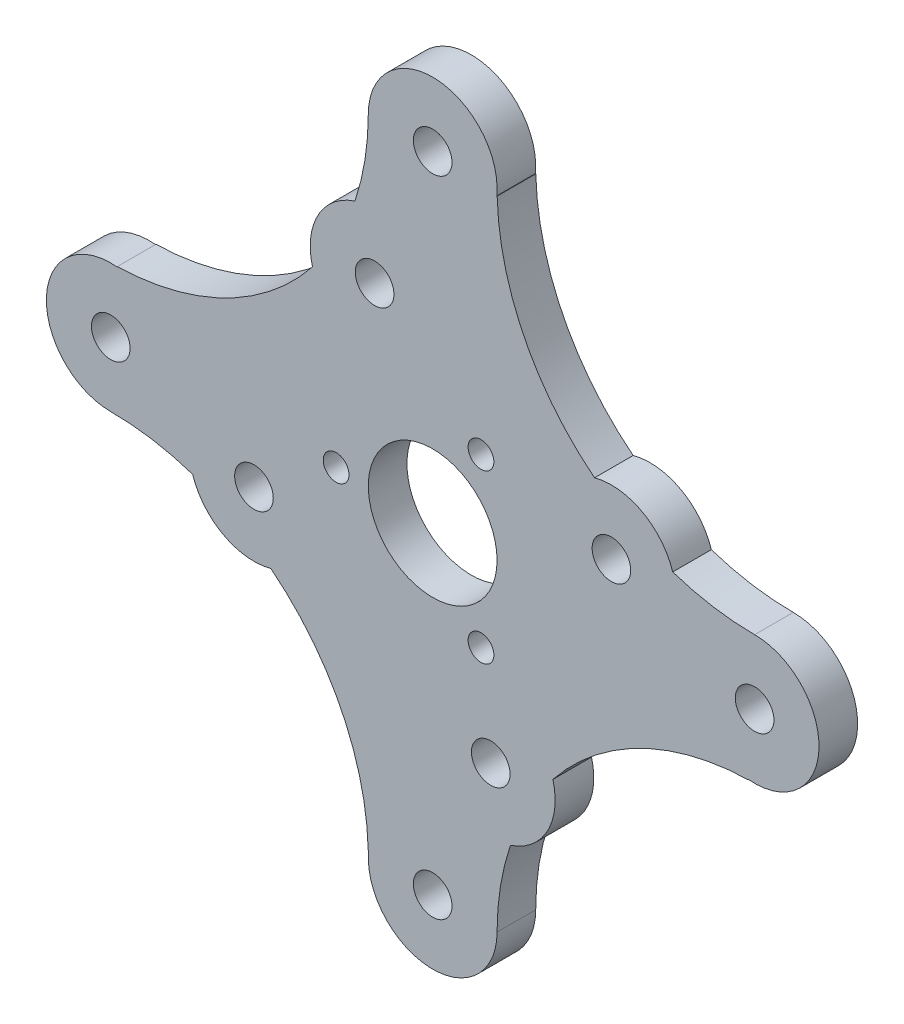
SolidWorks part; units mm, degrees
material "Acrílico (Impacto medio-alto)"
ref_plane "Alzado" through (0, 0, 0) normal (0, 0, 1) x (1, 0, 0)
ref_plane "Planta" through (0, 0, 0) normal (0, 1, 0) x (1, 0, 0)
ref_plane "Vista lateral" through (0, 0, 0) normal (1, 0, 0) x (0, 0, -1)
sketch "Croquis1" plane through (0, 0, 0) normal (0, 0, 1) x (1, 0, 0)
  line L0 (-25, 0) -> (0, 0) construction
  line L1 (0, 0) -> (-13.8797, -4.5098) construction
  line L2 (-13.8797, -4.5098) -> (-25, 0) construction
  line L3 (0, 25) -> (0, 0) construction
  line L4 (0, 0) -> (-4.5098, 13.8797) construction
  line L5 (-4.5098, 13.8797) -> (0, 25) construction
  line L6 (0, 0) -> (25, 0) construction
  line L7 (25, 0) -> (13.8797, 4.5098) construction
  line L8 (13.8797, 4.5098) -> (0, 0) construction
  line L9 (0, 0) -> (0, -25) construction
  line L10 (0, -25) -> (4.5098, -13.8797) construction
  line L11 (4.5098, -13.8797) -> (0, 0) construction
  circle A0 centre (0, 0) radius 25
  circle A1 centre (0, 25) radius 5
  circle A2 centre (25, 0) radius 5
  circle A3 centre (-25, 0) radius 5
  circle A4 centre (0, -25) radius 5
  arc A5 (-5, 25) -> (-25, 5) centre (-25, 25) cw
  arc A6 (5, 25) -> (25, 5) centre (25, 25) ccw
  arc A7 (25, -5) -> (5, -25) centre (25, -25) ccw
  arc A8 (-5, -25) -> (-25, -5) centre (-25, -25) ccw
  circle A9 centre (0, 25) radius 1.5
  circle A10 centre (25, 0) radius 1.5
  circle A11 centre (-25, 0) radius 1.5
  circle A12 centre (0, -25) radius 1.5
  circle A13 centre (0, 0) radius 5
  circle A14 centre (0, 0) radius 7.5
  circle A20 centre (-13.8797, -4.5098) radius 1.5
  circle A21 centre (-4.5098, 13.8797) radius 1.5
  circle A22 centre (13.8797, 4.5098) radius 1.5
  circle A23 centre (4.5098, -13.8797) radius 1.5
  circle A24 centre (-13.8797, -4.5098) radius 5
  circle A25 centre (-4.5098, 13.8797) radius 5
  circle A26 centre (13.8797, 4.5098) radius 5
  circle A27 centre (4.5098, -13.8797) radius 5
  dimension "D1" = 50
  dimension "D2" = 10
  dimension "D3" = 10
  dimension "D4" = 10
  dimension "D5" = 10
  dimension "D6" = 3
  dimension "D7" = 3
  dimension "D8" = 3
  dimension "D9" = 3
  dimension "D10" = 10
  dimension "D11" = 15
  dimension "D14" = 12
  dimension "D20" = 3
  dimension "D21" = 3
  dimension "D22" = 3
  dimension "D23" = 3
  dimension "D24" = 10
  dimension "D25" = 10
  dimension "D26" = 10
  dimension "D27" = 10
  dimension "D12" = 12
  dimension "D13" = 18
  dimension "D15" = 18
  dimension "D16" = 12
  dimension "D17" = 18
  dimension "D18" = 12
  dimension "D19" = 18
extrude "Saliente-Extruir1" add sketch "Croquis1" along normal blind 3 contours A11 A0 A3 | A11 A0 A3 | A20 A8 A24 | A9 A0 A1 | A9 A0 A1 | A21 A5 A25 | A22 A6 A26 | A10 A0 A2 | A10 A0 A2 | A27 A7 A0 A2 A26 A6 A1 A25 A5 A3 A24 A8 A4 A14 | A23 A7 A27 | A23 A7 A27 | A25 A1 A0 A5 | A21 A5 A25 | A24 A3 A0 A8 | A20 A8 A24 | A12 A0 A4 | A12 A0 A4 | A27 A4 A0 A7 | A26 A2 A0 A6 | A22 A6 A26 | A14 A13
sketch "Croquis2" plane through (0, 0, 3) normal (0, 0, 1) x (1, 0, 0)
  line L4 (-7.5, 0) -> (3.75, -6.4952)
  line L5 (3.75, -6.4952) -> (3.75, 6.4952)
  line L6 (3.75, 6.4952) -> (-7.5, 0)
  circle A0 centre (0, 0) radius 7.5
  circle A1 centre (0, 0) radius 5 construction
  circle A2 centre (0, 0) radius 3.75 construction
  circle A6 centre (3.75, 6.4952) radius 1
  circle A7 centre (3.75, -6.4952) radius 1
  circle A8 centre (-7.5, 0) radius 1
  dimension "D1" = 2.5
  dimension "D2" = 2
  dimension "D3" = 2
  dimension "D4" = 2
extrude "Cortar-Extruir2" cut sketch "Croquis2" against normal through all contours A6 | A8 | A7
